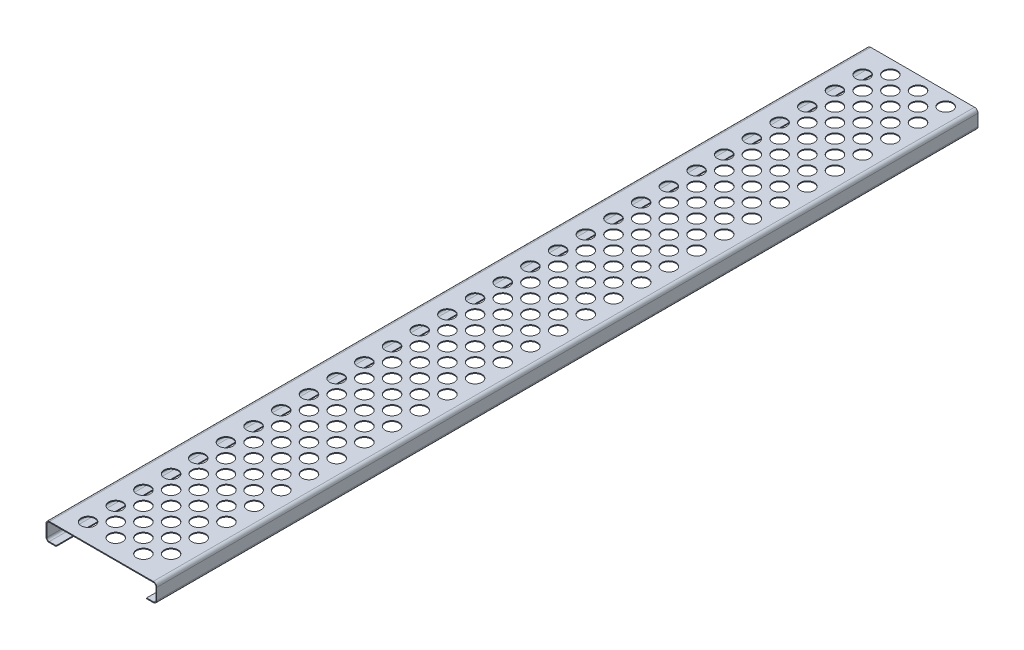
SolidWorks part; units mm, degrees
ref_plane "Front" through (0, 0, 0) normal (0, 0, 1) x (1, 0, 0)
ref_plane "Top" through (0, 0, 0) normal (0, 1, 0) x (1, 0, 0)
ref_plane "Right" through (0, 0, 0) normal (1, 0, 0) x (0, 0, -1)
sketch "Sketch1" plane through (0, 0, 0) normal (0, 0, 1) x (1, 0, 0)
  line L0 (-143.6688, 23.0187) -> (143.6687, 23.0187)
  line L1 (-142.875, 25.4) -> (142.875, 25.4)
  line L2 (-152.4, 15.875) -> (-152.4, -15.875)
  line L3 (-142.875, -25.4) -> (-124.6188, -25.4)
  line L4 (152.4, 15.875) -> (152.4, -15.875)
  line L5 (-152.4, 25.4) -> (152.4, -25.4) construction
  line L6 (-152.4, -25.4) -> (152.4, 25.4) construction
  line L7 (150.0187, 16.6687) -> (150.0187, -16.6688)
  line L8 (-143.6688, -23.0188) -> (-124.6188, -23.0188)
  line L9 (-150.0188, 16.6687) -> (-150.0188, -16.6688)
  line L10 (0, 0) -> (0, -25.4) construction
  line L11 (124.6187, -23.0188) -> (124.6187, -25.4)
  line L12 (-124.6188, -23.0188) -> (-124.6188, -25.4)
  line L13 (124.6187, -25.4) -> (142.875, -25.4)
  line L14 (-152.4, -25.4) -> (152.4, -25.4) construction
  line L15 (124.6187, -23.0188) -> (143.6687, -23.0188)
  line L16 (-150.0188, -23.0188) -> (150.0187, -23.0188) construction
  line L17 (-124.6188, 0) -> (-124.6188, -25.4) construction
  line L18 (124.6187, 0) -> (124.6187, -25.4) construction
  line L19 (150.0187, 23.0187) -> (150.0187, -23.0188) construction
  line L20 (-150.0188, 23.0187) -> (150.0187, 23.0187) construction
  line L21 (-150.0188, 23.0187) -> (-150.0188, -23.0188) construction
  line L22 (-152.4, 25.4) -> (-152.4, -25.4) construction
  line L23 (-152.4, 25.4) -> (152.4, 25.4) construction
  line L24 (152.4, 25.4) -> (152.4, -25.4) construction
  arc A0 (150.0187, -16.6688) -> (143.6687, -23.0188) centre (143.6687, -16.6688) cw
  arc A1 (150.0187, 16.6687) -> (143.6687, 23.0187) centre (143.6687, 16.6687) ccw
  arc A2 (-143.6688, 23.0187) -> (-150.0188, 16.6687) centre (-143.6688, 16.6687) ccw
  arc A3 (-150.0188, -16.6688) -> (-143.6688, -23.0188) centre (-143.6688, -16.6688) ccw
  arc A4 (-152.4, -15.875) -> (-142.875, -25.4) centre (-142.875, -15.875) ccw
  arc A5 (-152.4, 15.875) -> (-142.875, 25.4) centre (-142.875, 15.875) cw
  arc A6 (152.4, -15.875) -> (142.875, -25.4) centre (142.875, -15.875) cw
  arc A7 (152.4, 15.875) -> (142.875, 25.4) centre (142.875, 15.875) ccw
  point P0 (0, 0)
  dimension "D6" = 6.35
  dimension "D7" = 9.525
  dimension "D1" = 304.8
  dimension "D2" = 50.8
  dimension "D4" = 25.4
  dimension "D3" = 2.3813
extrude "Boss-Extrude1" add sketch "Sketch1" along normal blind 2260.6
sketch "Sketch2" plane through (0, 25.4, 0) normal (0, 1, 0) x (1, 0, 0)
  line L0 (142.875, 0) -> (-142.875, 0) construction
  line L1 (152.4, -2260.6) -> (152.4, 0) construction
  line L2 (114.3, -38.1) -> (76.2, -76.2) construction
  circle A0 centre (114.3, -38.1) radius 19.05
  circle A1 centre (76.2, -76.2) radius 19.05
  circle A2 centre (38.1, -38.1) radius 19.05
  circle A3 centre (0, -76.2) radius 19.05
  circle A4 centre (-38.1, -38.1) radius 19.05
  circle A5 centre (-76.2, -76.2) radius 19.05
  circle A6 centre (-114.3, -38.1) radius 19.05
  circle A7 centre (-152.4, -76.2) radius 19.05
  circle A8 centre (-190.5, -38.1) radius 19.05
  circle A9 centre (-228.6, -76.2) radius 19.05
  circle A10 centre (38.1, -114.3) radius 19.05
  circle A11 centre (0, -152.4) radius 19.05
  circle A12 centre (-38.1, -114.3) radius 19.05
  circle A13 centre (-76.2, -152.4) radius 19.05
  circle A14 centre (-114.3, -114.3) radius 19.05
  circle A15 centre (-152.4, -152.4) radius 19.05
  circle A16 centre (-190.5, -114.3) radius 19.05
  circle A17 centre (-228.6, -152.4) radius 19.05
  circle A18 centre (38.1, -190.5) radius 19.05
  circle A19 centre (0, -228.6) radius 19.05
  circle A20 centre (-38.1, -190.5) radius 19.05
  circle A21 centre (-76.2, -228.6) radius 19.05
  circle A22 centre (-114.3, -190.5) radius 19.05
  circle A23 centre (-152.4, -228.6) radius 19.05
  circle A24 centre (-190.5, -190.5) radius 19.05
  circle A25 centre (-228.6, -228.6) radius 19.05
  circle A26 centre (38.1, -266.7) radius 19.05
  circle A27 centre (0, -304.8) radius 19.05
  circle A28 centre (-38.1, -266.7) radius 19.05
  circle A29 centre (-76.2, -304.8) radius 19.05
  circle A30 centre (-114.3, -266.7) radius 19.05
  circle A31 centre (-152.4, -304.8) radius 19.05
  circle A32 centre (-190.5, -266.7) radius 19.05
  circle A33 centre (-228.6, -304.8) radius 19.05
  circle A34 centre (38.1, -342.9) radius 19.05
  circle A35 centre (0, -381) radius 19.05
  circle A36 centre (-38.1, -342.9) radius 19.05
  circle A37 centre (-76.2, -381) radius 19.05
  circle A38 centre (-114.3, -342.9) radius 19.05
  circle A39 centre (-152.4, -381) radius 19.05
  circle A40 centre (-190.5, -342.9) radius 19.05
  circle A41 centre (-228.6, -381) radius 19.05
  circle A42 centre (38.1, -419.1) radius 19.05
  circle A43 centre (0, -457.2) radius 19.05
  circle A44 centre (-38.1, -419.1) radius 19.05
  circle A45 centre (-76.2, -457.2) radius 19.05
  circle A46 centre (-114.3, -419.1) radius 19.05
  circle A47 centre (-152.4, -457.2) radius 19.05
  circle A48 centre (-190.5, -419.1) radius 19.05
  circle A49 centre (-228.6, -457.2) radius 19.05
  circle A50 centre (38.1, -495.3) radius 19.05
  circle A51 centre (0, -533.4) radius 19.05
  circle A52 centre (-38.1, -495.3) radius 19.05
  circle A53 centre (-76.2, -533.4) radius 19.05
  circle A54 centre (-114.3, -495.3) radius 19.05
  circle A55 centre (-152.4, -533.4) radius 19.05
  circle A56 centre (-190.5, -495.3) radius 19.05
  circle A57 centre (-228.6, -533.4) radius 19.05
  circle A58 centre (38.1, -571.5) radius 19.05
  circle A59 centre (0, -609.6) radius 19.05
  circle A60 centre (-38.1, -571.5) radius 19.05
  circle A61 centre (-76.2, -609.6) radius 19.05
  circle A62 centre (-114.3, -571.5) radius 19.05
  circle A63 centre (-152.4, -609.6) radius 19.05
  circle A64 centre (-190.5, -571.5) radius 19.05
  circle A65 centre (-228.6, -609.6) radius 19.05
  circle A66 centre (38.1, -647.7) radius 19.05
  circle A67 centre (0, -685.8) radius 19.05
  circle A68 centre (-38.1, -647.7) radius 19.05
  circle A69 centre (-76.2, -685.8) radius 19.05
  circle A70 centre (-114.3, -647.7) radius 19.05
  circle A71 centre (-152.4, -685.8) radius 19.05
  circle A72 centre (-190.5, -647.7) radius 19.05
  circle A73 centre (-228.6, -685.8) radius 19.05
  circle A74 centre (38.1, -723.9) radius 19.05
  circle A75 centre (0, -762) radius 19.05
  circle A76 centre (-38.1, -723.9) radius 19.05
  circle A77 centre (-76.2, -762) radius 19.05
  circle A78 centre (-114.3, -723.9) radius 19.05
  circle A79 centre (-152.4, -762) radius 19.05
  circle A80 centre (-190.5, -723.9) radius 19.05
  circle A81 centre (-228.6, -762) radius 19.05
  circle A82 centre (38.1, -800.1) radius 19.05
  circle A83 centre (0, -838.2) radius 19.05
  circle A84 centre (-38.1, -800.1) radius 19.05
  circle A85 centre (-76.2, -838.2) radius 19.05
  circle A86 centre (-114.3, -800.1) radius 19.05
  circle A87 centre (-152.4, -838.2) radius 19.05
  circle A88 centre (-190.5, -800.1) radius 19.05
  circle A89 centre (-228.6, -838.2) radius 19.05
  circle A90 centre (38.1, -876.3) radius 19.05
  circle A91 centre (0, -914.4) radius 19.05
  circle A92 centre (-38.1, -876.3) radius 19.05
  circle A93 centre (-76.2, -914.4) radius 19.05
  circle A94 centre (-114.3, -876.3) radius 19.05
  circle A95 centre (-152.4, -914.4) radius 19.05
  circle A96 centre (-190.5, -876.3) radius 19.05
  circle A97 centre (-228.6, -914.4) radius 19.05
  circle A98 centre (38.1, -952.5) radius 19.05
  circle A99 centre (0, -990.6) radius 19.05
  circle A100 centre (-38.1, -952.5) radius 19.05
  circle A101 centre (-76.2, -990.6) radius 19.05
  circle A102 centre (-114.3, -952.5) radius 19.05
  circle A103 centre (-152.4, -990.6) radius 19.05
  circle A104 centre (-190.5, -952.5) radius 19.05
  circle A105 centre (-228.6, -990.6) radius 19.05
  circle A106 centre (38.1, -1028.7) radius 19.05
  circle A107 centre (0, -1066.8) radius 19.05
  circle A108 centre (-38.1, -1028.7) radius 19.05
  circle A109 centre (-76.2, -1066.8) radius 19.05
  circle A110 centre (-114.3, -1028.7) radius 19.05
  circle A111 centre (-152.4, -1066.8) radius 19.05
  circle A112 centre (-190.5, -1028.7) radius 19.05
  circle A113 centre (-228.6, -1066.8) radius 19.05
  circle A114 centre (38.1, -1104.9) radius 19.05
  circle A115 centre (0, -1143) radius 19.05
  circle A116 centre (-38.1, -1104.9) radius 19.05
  circle A117 centre (-76.2, -1143) radius 19.05
  circle A118 centre (-114.3, -1104.9) radius 19.05
  circle A119 centre (-152.4, -1143) radius 19.05
  circle A120 centre (-190.5, -1104.9) radius 19.05
  circle A121 centre (-228.6, -1143) radius 19.05
  circle A122 centre (38.1, -1181.1) radius 19.05
  circle A123 centre (0, -1219.2) radius 19.05
  circle A124 centre (-38.1, -1181.1) radius 19.05
  circle A125 centre (-76.2, -1219.2) radius 19.05
  circle A126 centre (-114.3, -1181.1) radius 19.05
  circle A127 centre (-152.4, -1219.2) radius 19.05
  circle A128 centre (-190.5, -1181.1) radius 19.05
  circle A129 centre (-228.6, -1219.2) radius 19.05
  circle A130 centre (38.1, -1257.3) radius 19.05
  circle A131 centre (0, -1295.4) radius 19.05
  circle A132 centre (-38.1, -1257.3) radius 19.05
  circle A133 centre (-76.2, -1295.4) radius 19.05
  circle A134 centre (-114.3, -1257.3) radius 19.05
  circle A135 centre (-152.4, -1295.4) radius 19.05
  circle A136 centre (-190.5, -1257.3) radius 19.05
  circle A137 centre (-228.6, -1295.4) radius 19.05
  circle A138 centre (38.1, -1333.5) radius 19.05
  circle A139 centre (0, -1371.6) radius 19.05
  circle A140 centre (-38.1, -1333.5) radius 19.05
  circle A141 centre (-76.2, -1371.6) radius 19.05
  circle A142 centre (-114.3, -1333.5) radius 19.05
  circle A143 centre (-152.4, -1371.6) radius 19.05
  circle A144 centre (-190.5, -1333.5) radius 19.05
  circle A145 centre (-228.6, -1371.6) radius 19.05
  circle A146 centre (38.1, -1409.7) radius 19.05
  circle A147 centre (0, -1447.8) radius 19.05
  circle A148 centre (-38.1, -1409.7) radius 19.05
  circle A149 centre (-76.2, -1447.8) radius 19.05
  circle A150 centre (-114.3, -1409.7) radius 19.05
  circle A151 centre (-152.4, -1447.8) radius 19.05
  circle A152 centre (-190.5, -1409.7) radius 19.05
  circle A153 centre (-228.6, -1447.8) radius 19.05
  circle A154 centre (38.1, -1485.9) radius 19.05
  circle A155 centre (0, -1524) radius 19.05
  circle A156 centre (-38.1, -1485.9) radius 19.05
  circle A157 centre (-76.2, -1524) radius 19.05
  circle A158 centre (-114.3, -1485.9) radius 19.05
  circle A159 centre (-152.4, -1524) radius 19.05
  circle A160 centre (-190.5, -1485.9) radius 19.05
  circle A161 centre (-228.6, -1524) radius 19.05
  circle A162 centre (38.1, -1562.1) radius 19.05
  circle A163 centre (0, -1600.2) radius 19.05
  circle A164 centre (-38.1, -1562.1) radius 19.05
  circle A165 centre (-76.2, -1600.2) radius 19.05
  circle A166 centre (-114.3, -1562.1) radius 19.05
  circle A167 centre (-152.4, -1600.2) radius 19.05
  circle A168 centre (-190.5, -1562.1) radius 19.05
  circle A169 centre (-228.6, -1600.2) radius 19.05
  circle A170 centre (38.1, -1638.3) radius 19.05
  circle A171 centre (0, -1676.4) radius 19.05
  circle A172 centre (-38.1, -1638.3) radius 19.05
  circle A173 centre (-76.2, -1676.4) radius 19.05
  circle A174 centre (-114.3, -1638.3) radius 19.05
  circle A175 centre (-152.4, -1676.4) radius 19.05
  circle A176 centre (-190.5, -1638.3) radius 19.05
  circle A177 centre (-228.6, -1676.4) radius 19.05
  circle A178 centre (38.1, -1714.5) radius 19.05
  circle A179 centre (0, -1752.6) radius 19.05
  circle A180 centre (-38.1, -1714.5) radius 19.05
  circle A181 centre (-76.2, -1752.6) radius 19.05
  circle A182 centre (-114.3, -1714.5) radius 19.05
  circle A183 centre (-152.4, -1752.6) radius 19.05
  circle A184 centre (-190.5, -1714.5) radius 19.05
  circle A185 centre (-228.6, -1752.6) radius 19.05
  circle A186 centre (38.1, -1790.7) radius 19.05
  circle A187 centre (0, -1828.8) radius 19.05
  circle A188 centre (-38.1, -1790.7) radius 19.05
  circle A189 centre (-76.2, -1828.8) radius 19.05
  circle A190 centre (-114.3, -1790.7) radius 19.05
  circle A191 centre (-152.4, -1828.8) radius 19.05
  circle A192 centre (-190.5, -1790.7) radius 19.05
  circle A193 centre (-228.6, -1828.8) radius 19.05
  circle A194 centre (38.1, -1866.9) radius 19.05
  circle A195 centre (0, -1905) radius 19.05
  circle A196 centre (-38.1, -1866.9) radius 19.05
  circle A197 centre (-76.2, -1905) radius 19.05
  circle A198 centre (-114.3, -1866.9) radius 19.05
  circle A199 centre (-152.4, -1905) radius 19.05
  circle A200 centre (-190.5, -1866.9) radius 19.05
  circle A201 centre (-228.6, -1905) radius 19.05
  circle A202 centre (38.1, -1943.1) radius 19.05
  circle A203 centre (0, -1981.2) radius 19.05
  circle A204 centre (-38.1, -1943.1) radius 19.05
  circle A205 centre (-76.2, -1981.2) radius 19.05
  circle A206 centre (-114.3, -1943.1) radius 19.05
  circle A207 centre (-152.4, -1981.2) radius 19.05
  circle A208 centre (-190.5, -1943.1) radius 19.05
  circle A209 centre (-228.6, -1981.2) radius 19.05
  circle A210 centre (38.1, -2019.3) radius 19.05
  circle A211 centre (0, -2057.4) radius 19.05
  circle A212 centre (-38.1, -2019.3) radius 19.05
  circle A213 centre (-76.2, -2057.4) radius 19.05
  circle A214 centre (-114.3, -2019.3) radius 19.05
  circle A215 centre (-152.4, -2057.4) radius 19.05
  circle A216 centre (-190.5, -2019.3) radius 19.05
  circle A217 centre (-228.6, -2057.4) radius 19.05
  circle A218 centre (38.1, -2095.5) radius 19.05
  circle A219 centre (0, -2133.6) radius 19.05
  circle A220 centre (-38.1, -2095.5) radius 19.05
  circle A221 centre (-76.2, -2133.6) radius 19.05
  circle A222 centre (-114.3, -2095.5) radius 19.05
  circle A223 centre (-152.4, -2133.6) radius 19.05
  circle A224 centre (-190.5, -2095.5) radius 19.05
  circle A225 centre (-228.6, -2133.6) radius 19.05
  circle A226 centre (38.1, -2171.7) radius 19.05
  circle A227 centre (0, -2209.8) radius 19.05
  circle A228 centre (-38.1, -2171.7) radius 19.05
  circle A229 centre (-76.2, -2209.8) radius 19.05
  circle A230 centre (-114.3, -2171.7) radius 19.05
  circle A231 centre (-152.4, -2209.8) radius 19.05
  circle A232 centre (-190.5, -2171.7) radius 19.05
  circle A233 centre (-228.6, -2209.8) radius 19.05
  circle A234 centre (114.3, -114.3) radius 19.05
  circle A235 centre (76.2, -152.4) radius 19.05
  circle A236 centre (114.3, -190.5) radius 19.05
  circle A237 centre (76.2, -228.6) radius 19.05
  circle A238 centre (114.3, -266.7) radius 19.05
  circle A239 centre (76.2, -304.8) radius 19.05
  circle A240 centre (114.3, -342.9) radius 19.05
  circle A241 centre (76.2, -381) radius 19.05
  circle A242 centre (114.3, -419.1) radius 19.05
  circle A243 centre (76.2, -457.2) radius 19.05
  circle A244 centre (114.3, -495.3) radius 19.05
  circle A245 centre (76.2, -533.4) radius 19.05
  circle A246 centre (114.3, -571.5) radius 19.05
  circle A247 centre (76.2, -609.6) radius 19.05
  circle A248 centre (114.3, -647.7) radius 19.05
  circle A249 centre (76.2, -685.8) radius 19.05
  circle A250 centre (114.3, -723.9) radius 19.05
  circle A251 centre (76.2, -762) radius 19.05
  circle A252 centre (114.3, -800.1) radius 19.05
  circle A253 centre (76.2, -838.2) radius 19.05
  circle A254 centre (114.3, -876.3) radius 19.05
  circle A255 centre (76.2, -914.4) radius 19.05
  circle A256 centre (114.3, -952.5) radius 19.05
  circle A257 centre (76.2, -990.6) radius 19.05
  circle A258 centre (114.3, -1028.7) radius 19.05
  circle A259 centre (76.2, -1066.8) radius 19.05
  circle A260 centre (114.3, -1104.9) radius 19.05
  circle A261 centre (76.2, -1143) radius 19.05
  circle A262 centre (114.3, -1181.1) radius 19.05
  circle A263 centre (76.2, -1219.2) radius 19.05
  circle A264 centre (114.3, -1257.3) radius 19.05
  circle A265 centre (76.2, -1295.4) radius 19.05
  circle A266 centre (114.3, -1333.5) radius 19.05
  circle A267 centre (76.2, -1371.6) radius 19.05
  circle A268 centre (114.3, -1409.7) radius 19.05
  circle A269 centre (76.2, -1447.8) radius 19.05
  circle A270 centre (114.3, -1485.9) radius 19.05
  circle A271 centre (76.2, -1524) radius 19.05
  circle A272 centre (114.3, -1562.1) radius 19.05
  circle A273 centre (76.2, -1600.2) radius 19.05
  circle A274 centre (114.3, -1638.3) radius 19.05
  circle A275 centre (76.2, -1676.4) radius 19.05
  circle A276 centre (114.3, -1714.5) radius 19.05
  circle A277 centre (76.2, -1752.6) radius 19.05
  circle A278 centre (114.3, -1790.7) radius 19.05
  circle A279 centre (76.2, -1828.8) radius 19.05
  circle A280 centre (114.3, -1866.9) radius 19.05
  circle A281 centre (76.2, -1905) radius 19.05
  circle A282 centre (114.3, -1943.1) radius 19.05
  circle A283 centre (76.2, -1981.2) radius 19.05
  circle A284 centre (114.3, -2019.3) radius 19.05
  circle A285 centre (76.2, -2057.4) radius 19.05
  circle A286 centre (114.3, -2095.5) radius 19.05
  circle A287 centre (76.2, -2133.6) radius 19.05
  circle A288 centre (114.3, -2171.7) radius 19.05
  circle A289 centre (76.2, -2209.8) radius 19.05
  dimension "D1" = 38.1
  dimension "D4" = 45
  dimension "D2" = 38.1
  dimension "D3" = 38.1
  dimension "D5" = 38.1
  dimension "D6" = 5
  dimension "D7" = 29
extrude "Cut-Extrude1" [suppressed] cut sketch "Sketch2" against normal up to next
sketch "Sketch3" plane through (0, 25.4, 0) normal (0, 1, 0) x (1, 0, 0)
  line L0 (101.6, -38.1) -> (63.5, -76.2) construction
  line L2 (152.4, -2260.6) -> (152.4, 0) construction
  line L3 (-143.6688, 0) -> (143.6687, 0) construction
  circle A0 centre (101.6, -38.1) radius 19.05
  circle A1 centre (63.5, -76.2) radius 19.05
  circle A3 centre (-12.7, -76.2) radius 19.05
  circle A4 centre (25.4, -38.1) radius 19.05
  circle A5 centre (-88.9, -76.2) radius 19.05
  circle A6 centre (-50.8, -38.1) radius 19.05
  circle A9 centre (-12.7, -152.4) radius 19.05
  circle A10 centre (25.4, -114.3) radius 19.05
  circle A11 centre (-88.9, -152.4) radius 19.05
  circle A12 centre (-50.8, -114.3) radius 19.05
  circle A15 centre (-12.7, -228.6) radius 19.05
  circle A16 centre (25.4, -190.5) radius 19.05
  circle A17 centre (-88.9, -228.6) radius 19.05
  circle A18 centre (-50.8, -190.5) radius 19.05
  circle A21 centre (-12.7, -304.8) radius 19.05
  circle A22 centre (25.4, -266.7) radius 19.05
  circle A23 centre (-88.9, -304.8) radius 19.05
  circle A24 centre (-50.8, -266.7) radius 19.05
  circle A27 centre (-12.7, -381) radius 19.05
  circle A28 centre (25.4, -342.9) radius 19.05
  circle A29 centre (-88.9, -381) radius 19.05
  circle A30 centre (-50.8, -342.9) radius 19.05
  circle A33 centre (-12.7, -457.2) radius 19.05
  circle A34 centre (25.4, -419.1) radius 19.05
  circle A35 centre (-88.9, -457.2) radius 19.05
  circle A36 centre (-50.8, -419.1) radius 19.05
  circle A39 centre (-12.7, -533.4) radius 19.05
  circle A40 centre (25.4, -495.3) radius 19.05
  circle A41 centre (-88.9, -533.4) radius 19.05
  circle A42 centre (-50.8, -495.3) radius 19.05
  circle A45 centre (-12.7, -609.6) radius 19.05
  circle A46 centre (25.4, -571.5) radius 19.05
  circle A47 centre (-88.9, -609.6) radius 19.05
  circle A48 centre (-50.8, -571.5) radius 19.05
  circle A51 centre (-12.7, -685.8) radius 19.05
  circle A52 centre (25.4, -647.7) radius 19.05
  circle A53 centre (-88.9, -685.8) radius 19.05
  circle A54 centre (-50.8, -647.7) radius 19.05
  circle A57 centre (-12.7, -762) radius 19.05
  circle A58 centre (25.4, -723.9) radius 19.05
  circle A59 centre (-88.9, -762) radius 19.05
  circle A60 centre (-50.8, -723.9) radius 19.05
  circle A63 centre (-12.7, -838.2) radius 19.05
  circle A64 centre (25.4, -800.1) radius 19.05
  circle A65 centre (-88.9, -838.2) radius 19.05
  circle A66 centre (-50.8, -800.1) radius 19.05
  circle A69 centre (-12.7, -914.4) radius 19.05
  circle A70 centre (25.4, -876.3) radius 19.05
  circle A71 centre (-88.9, -914.4) radius 19.05
  circle A72 centre (-50.8, -876.3) radius 19.05
  circle A75 centre (-12.7, -990.6) radius 19.05
  circle A76 centre (25.4, -952.5) radius 19.05
  circle A77 centre (-88.9, -990.6) radius 19.05
  circle A78 centre (-50.8, -952.5) radius 19.05
  circle A81 centre (-12.7, -1066.8) radius 19.05
  circle A82 centre (25.4, -1028.7) radius 19.05
  circle A83 centre (-88.9, -1066.8) radius 19.05
  circle A84 centre (-50.8, -1028.7) radius 19.05
  circle A87 centre (-12.7, -1143) radius 19.05
  circle A88 centre (25.4, -1104.9) radius 19.05
  circle A89 centre (-88.9, -1143) radius 19.05
  circle A90 centre (-50.8, -1104.9) radius 19.05
  circle A93 centre (-12.7, -1219.2) radius 19.05
  circle A94 centre (25.4, -1181.1) radius 19.05
  circle A95 centre (-88.9, -1219.2) radius 19.05
  circle A96 centre (-50.8, -1181.1) radius 19.05
  circle A99 centre (-12.7, -1295.4) radius 19.05
  circle A100 centre (25.4, -1257.3) radius 19.05
  circle A101 centre (-88.9, -1295.4) radius 19.05
  circle A102 centre (-50.8, -1257.3) radius 19.05
  circle A105 centre (-12.7, -1371.6) radius 19.05
  circle A106 centre (25.4, -1333.5) radius 19.05
  circle A107 centre (-88.9, -1371.6) radius 19.05
  circle A108 centre (-50.8, -1333.5) radius 19.05
  circle A111 centre (-12.7, -1447.8) radius 19.05
  circle A112 centre (25.4, -1409.7) radius 19.05
  circle A113 centre (-88.9, -1447.8) radius 19.05
  circle A114 centre (-50.8, -1409.7) radius 19.05
  circle A117 centre (-12.7, -1524) radius 19.05
  circle A118 centre (25.4, -1485.9) radius 19.05
  circle A119 centre (-88.9, -1524) radius 19.05
  circle A120 centre (-50.8, -1485.9) radius 19.05
  circle A123 centre (-12.7, -1600.2) radius 19.05
  circle A124 centre (25.4, -1562.1) radius 19.05
  circle A125 centre (-88.9, -1600.2) radius 19.05
  circle A126 centre (-50.8, -1562.1) radius 19.05
  circle A129 centre (-12.7, -1676.4) radius 19.05
  circle A130 centre (25.4, -1638.3) radius 19.05
  circle A131 centre (-88.9, -1676.4) radius 19.05
  circle A132 centre (-50.8, -1638.3) radius 19.05
  circle A135 centre (-12.7, -1752.6) radius 19.05
  circle A136 centre (25.4, -1714.5) radius 19.05
  circle A137 centre (-88.9, -1752.6) radius 19.05
  circle A138 centre (-50.8, -1714.5) radius 19.05
  circle A141 centre (-12.7, -1828.8) radius 19.05
  circle A142 centre (25.4, -1790.7) radius 19.05
  circle A143 centre (-88.9, -1828.8) radius 19.05
  circle A144 centre (-50.8, -1790.7) radius 19.05
  circle A147 centre (-12.7, -1905) radius 19.05
  circle A148 centre (25.4, -1866.9) radius 19.05
  circle A149 centre (-88.9, -1905) radius 19.05
  circle A150 centre (-50.8, -1866.9) radius 19.05
  circle A153 centre (63.5, -152.4) radius 19.05
  circle A154 centre (101.6, -114.3) radius 19.05
  circle A155 centre (63.5, -228.6) radius 19.05
  circle A156 centre (101.6, -190.5) radius 19.05
  circle A157 centre (63.5, -304.8) radius 19.05
  circle A158 centre (101.6, -266.7) radius 19.05
  circle A159 centre (63.5, -381) radius 19.05
  circle A160 centre (101.6, -342.9) radius 19.05
  circle A161 centre (63.5, -457.2) radius 19.05
  circle A162 centre (101.6, -419.1) radius 19.05
  circle A163 centre (63.5, -533.4) radius 19.05
  circle A164 centre (101.6, -495.3) radius 19.05
  circle A165 centre (63.5, -609.6) radius 19.05
  circle A166 centre (101.6, -571.5) radius 19.05
  circle A167 centre (63.5, -685.8) radius 19.05
  circle A168 centre (101.6, -647.7) radius 19.05
  circle A169 centre (63.5, -762) radius 19.05
  circle A170 centre (101.6, -723.9) radius 19.05
  circle A171 centre (63.5, -838.2) radius 19.05
  circle A172 centre (101.6, -800.1) radius 19.05
  circle A173 centre (63.5, -914.4) radius 19.05
  circle A174 centre (101.6, -876.3) radius 19.05
  circle A175 centre (63.5, -990.6) radius 19.05
  circle A176 centre (101.6, -952.5) radius 19.05
  circle A177 centre (63.5, -1066.8) radius 19.05
  circle A178 centre (101.6, -1028.7) radius 19.05
  circle A179 centre (63.5, -1143) radius 19.05
  circle A180 centre (101.6, -1104.9) radius 19.05
  circle A181 centre (63.5, -1219.2) radius 19.05
  circle A182 centre (101.6, -1181.1) radius 19.05
  circle A183 centre (63.5, -1295.4) radius 19.05
  circle A184 centre (101.6, -1257.3) radius 19.05
  circle A185 centre (63.5, -1371.6) radius 19.05
  circle A186 centre (101.6, -1333.5) radius 19.05
  circle A187 centre (63.5, -1447.8) radius 19.05
  circle A188 centre (101.6, -1409.7) radius 19.05
  circle A189 centre (63.5, -1524) radius 19.05
  circle A190 centre (101.6, -1485.9) radius 19.05
  circle A191 centre (63.5, -1600.2) radius 19.05
  circle A192 centre (101.6, -1562.1) radius 19.05
  circle A193 centre (63.5, -1676.4) radius 19.05
  circle A194 centre (101.6, -1638.3) radius 19.05
  circle A195 centre (63.5, -1752.6) radius 19.05
  circle A196 centre (101.6, -1714.5) radius 19.05
  circle A197 centre (63.5, -1828.8) radius 19.05
  circle A198 centre (101.6, -1790.7) radius 19.05
  circle A199 centre (63.5, -1905) radius 19.05
  circle A200 centre (101.6, -1866.9) radius 19.05
  circle A201 centre (-165.1, -76.2) radius 19.05 [skipped]
  circle A202 centre (-165.1, -152.4) radius 19.05 [skipped]
  circle A203 centre (-165.1, -228.6) radius 19.05 [skipped]
  circle A204 centre (-165.1, -304.8) radius 19.05 [skipped]
  circle A205 centre (-165.1, -381) radius 19.05 [skipped]
  circle A206 centre (-165.1, -457.2) radius 19.05 [skipped]
  circle A207 centre (-165.1, -533.4) radius 19.05 [skipped]
  circle A208 centre (-165.1, -609.6) radius 19.05 [skipped]
  circle A209 centre (-165.1, -685.8) radius 19.05 [skipped]
  circle A210 centre (-165.1, -762) radius 19.05 [skipped]
  circle A211 centre (-165.1, -838.2) radius 19.05 [skipped]
  circle A212 centre (-165.1, -914.4) radius 19.05 [skipped]
  circle A213 centre (-165.1, -990.6) radius 19.05 [skipped]
  circle A214 centre (-165.1, -1066.8) radius 19.05 [skipped]
  circle A215 centre (-165.1, -1143) radius 19.05 [skipped]
  circle A216 centre (-165.1, -1219.2) radius 19.05 [skipped]
  circle A217 centre (-165.1, -1295.4) radius 19.05 [skipped]
  circle A218 centre (-165.1, -1371.6) radius 19.05 [skipped]
  circle A219 centre (-127, -38.1) radius 19.05 [skipped]
  circle A220 centre (-127, -114.3) radius 19.05 [skipped]
  circle A221 centre (-127, -190.5) radius 19.05 [skipped]
  circle A222 centre (-127, -266.7) radius 19.05 [skipped]
  circle A223 centre (-127, -342.9) radius 19.05 [skipped]
  circle A224 centre (-127, -419.1) radius 19.05 [skipped]
  circle A225 centre (-127, -495.3) radius 19.05 [skipped]
  circle A226 centre (-127, -571.5) radius 19.05 [skipped]
  circle A227 centre (-127, -647.7) radius 19.05 [skipped]
  circle A228 centre (-127, -723.9) radius 19.05 [skipped]
  circle A229 centre (-127, -800.1) radius 19.05 [skipped]
  circle A230 centre (-127, -876.3) radius 19.05 [skipped]
  circle A231 centre (-127, -952.5) radius 19.05 [skipped]
  circle A232 centre (-127, -1028.7) radius 19.05 [skipped]
  circle A233 centre (-127, -1104.9) radius 19.05 [skipped]
  circle A234 centre (-127, -1181.1) radius 19.05 [skipped]
  circle A235 centre (-127, -1257.3) radius 19.05 [skipped]
  circle A236 centre (-127, -1333.5) radius 19.05 [skipped]
  circle A237 centre (-165.1, -1447.8) radius 19.05 [skipped]
  circle A238 centre (-127, -1409.7) radius 19.05 [skipped]
  circle A239 centre (-165.1, -1524) radius 19.05 [skipped]
  circle A240 centre (-127, -1485.9) radius 19.05 [skipped]
  circle A241 centre (-165.1, -1600.2) radius 19.05 [skipped]
  circle A242 centre (-127, -1562.1) radius 19.05 [skipped]
  circle A243 centre (-165.1, -1676.4) radius 19.05 [skipped]
  circle A244 centre (-127, -1638.3) radius 19.05 [skipped]
  circle A245 centre (-165.1, -1752.6) radius 19.05 [skipped]
  circle A246 centre (-127, -1714.5) radius 19.05 [skipped]
  circle A247 centre (-165.1, -1828.8) radius 19.05 [skipped]
  circle A248 centre (-127, -1790.7) radius 19.05 [skipped]
  circle A249 centre (-165.1, -1905) radius 19.05 [skipped]
  circle A250 centre (-127, -1866.9) radius 19.05 [skipped]
  circle A253 centre (-12.7, -1979.7351) radius 19.05
  circle A254 centre (25.4, -1941.6351) radius 19.05
  circle A255 centre (-88.9, -1979.7351) radius 19.05
  circle A256 centre (-50.8, -1941.6351) radius 19.05
  circle A257 centre (-12.7, -2055.9351) radius 19.05
  circle A258 centre (25.4, -2017.8351) radius 19.05
  circle A259 centre (-88.9, -2055.9351) radius 19.05
  circle A260 centre (-50.8, -2017.8351) radius 19.05
  circle A261 centre (-12.7, -2132.1351) radius 19.05
  circle A262 centre (25.4, -2094.0351) radius 19.05
  circle A263 centre (-88.9, -2132.1351) radius 19.05
  circle A264 centre (-50.8, -2094.0351) radius 19.05
  circle A265 centre (-12.7, -2208.3351) radius 19.05
  circle A266 centre (25.4, -2170.2351) radius 19.05
  circle A267 centre (-88.9, -2208.3351) radius 19.05
  circle A268 centre (-50.8, -2170.2351) radius 19.05
  circle A282 centre (63.5, -1979.7351) radius 19.05
  circle A283 centre (101.6, -1941.6351) radius 19.05
  circle A284 centre (63.5, -2055.9351) radius 19.05
  circle A285 centre (101.6, -2017.8351) radius 19.05
  circle A286 centre (63.5, -2132.1351) radius 19.05
  circle A287 centre (101.6, -2094.0351) radius 19.05
  circle A288 centre (63.5, -2208.3351) radius 19.05
  circle A289 centre (101.6, -2170.2351) radius 19.05
  dimension "D1" = 38.1
  dimension "D2" = 38.1
  dimension "D3" = 38.1
  dimension "D4" = 50.8
  dimension "D5" = 38.1
  dimension "D6" = 4
  dimension "D7" = 25
extrude "Cut-Extrude2" cut sketch "Sketch3" against normal through all
